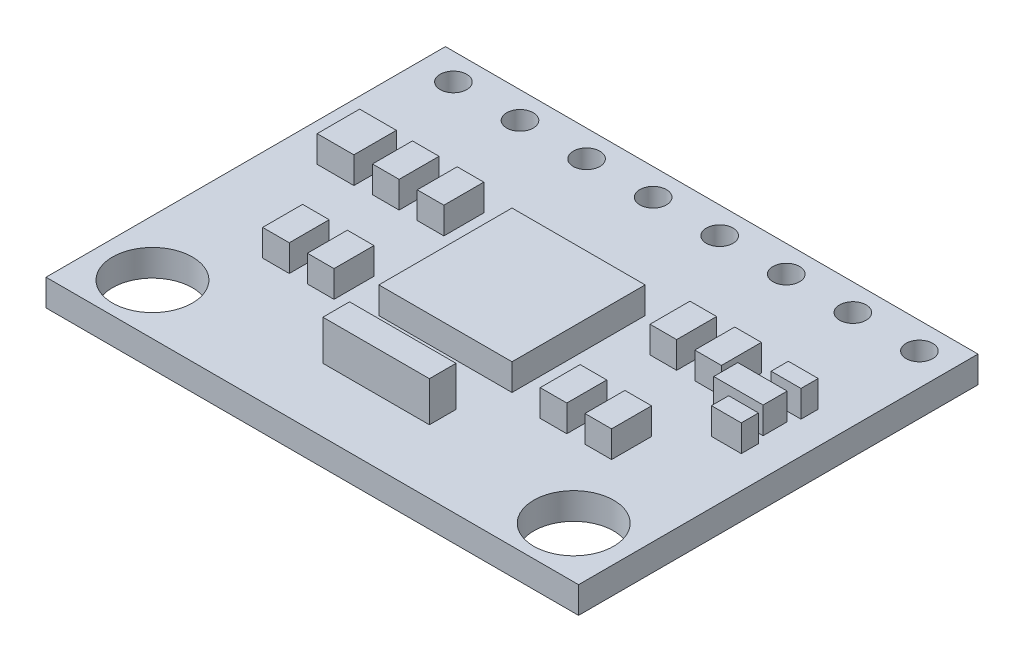
SolidWorks part; units mm, degrees
ref_plane "Front Plane" through (0, 0, 0) normal (0, 0, 1) x (1, 0, 0)
ref_plane "Top Plane" through (0, 0, 0) normal (0, 1, 0) x (1, 0, 0)
ref_plane "Right Plane" through (0, 0, 0) normal (1, 0, 0) x (0, 0, -1)
sketch "Sketch1" plane through (0, 0, 0) normal (0, 1, 0) x (1, 0, 0)
  line L1 (-10, 7.5) -> (10, 7.5)
  line L2 (-10, 7.5) -> (-10, -7.5)
  line L3 (-10, -7.5) -> (10, -7.5)
  line L4 (10, 7.5) -> (10, -7.5)
  line L5 (-10, 7.5) -> (10, -7.5) construction
  line L6 (-10, -7.5) -> (10, 7.5) construction
  point P0 (0, 0)
  dimension "D1" = 15
  dimension "D2" = 20
extrude "Boss-Extrude1" add sketch "Sketch1" along normal blind 1
sketch "Sketch2" plane through (0, 1, 0) normal (0, 1, 0) x (1, 0, 0)
  line L0 (10, 7.5) -> (-10, 7.5) construction
  line L1 (10, -7.5) -> (10, 7.5) construction
  circle A0 centre (8.8, 6.5) radius 0.5
  circle A1 centre (6.3, 6.5) radius 0.5
  circle A2 centre (3.8, 6.5) radius 0.5
  circle A3 centre (1.3, 6.5) radius 0.5
  circle A4 centre (-1.2, 6.5) radius 0.5
  circle A5 centre (-3.7, 6.5) radius 0.5
  circle A6 centre (-6.2, 6.5) radius 0.5
  circle A7 centre (-8.7, 6.5) radius 0.5
  dimension "D1" = 1
  dimension "D2" = 1
  dimension "D4" = 1.2
  dimension "D3" = 8
extrude "Cut-Extrude1" cut sketch "Sketch2" against normal blind 1
sketch "Sketch3" plane through (0, 1, 0) normal (0, 1, 0) x (1, 0, 0)
  circle A0 centre (7.9097, -5.5929) radius 1.5
  circle A1 centre (-7.9097, -5.5929) radius 1.5
  point P6 (0, 4.7739)
  dimension "D1" = 3
extrude "Cut-Extrude2" cut sketch "Sketch3" against normal blind 1
sketch "Sketch4" plane through (0, 1, 0) normal (0, 1, 0) x (1, 0, 0)
  line L1 (-2.5, 2.5) -> (2.5, 2.5)
  line L2 (-2.5, 2.5) -> (-2.5, -2.5)
  line L3 (-2.5, -2.5) -> (2.5, -2.5)
  line L4 (2.5, 2.5) -> (2.5, -2.5)
  line L5 (-2.5, 2.5) -> (2.5, -2.5) construction
  line L6 (-2.5, -2.5) -> (2.5, 2.5) construction
  point P0 (0, 0)
  dimension "D1" = 5
  dimension "D2" = 5
extrude "Boss-Extrude2" add sketch "Sketch4" along normal blind 1
sketch "Sketch5" plane through (0, 1, 0) normal (0, 1, 0) x (1, 0, 0)
  line L0 (0, 4.3428) -> (0, -4.6014) construction
  line L2 (-2, -4.1014) -> (2, -4.1014)
  line L3 (-2, -4.1014) -> (-2, -5.1014)
  line L4 (-2, -5.1014) -> (2, -5.1014)
  line L5 (2, -4.1014) -> (2, -5.1014)
  line L6 (-2, -4.1014) -> (2, -5.1014) construction
  line L7 (-2, -5.1014) -> (2, -4.1014) construction
  dimension "D1" = 4
  dimension "D2" = 1
extrude "Boss-Extrude3" add sketch "Sketch5" along normal blind 1.5
sketch "Sketch6" plane through (0, 1, 0) normal (0, 1, 0) x (1, 0, 0)
  line L0 (0, 8.0067) -> (0, -8.5671) construction
  line L1 (-13.5996, 0) -> (10.884, 0)
  line L2 (-3.8708, -2.8126) -> (-3.8708, -1.3126)
  line L3 (-4.8708, 2.8126) -> (-3.8708, 2.8126)
  line L4 (-4.8708, 2.8126) -> (-4.8708, 1.3126)
  line L5 (-4.8708, 1.3126) -> (-3.8708, 1.3126)
  line L6 (-3.8708, 2.8126) -> (-3.8708, 1.3126)
  line L9 (-6.5519, 2.8126) -> (-5.5519, 2.8126)
  line L10 (-6.5519, 2.8126) -> (-6.5519, 1.3126)
  line L11 (-6.5519, 1.3126) -> (-5.5519, 1.3126)
  line L12 (-5.5519, 2.8126) -> (-5.5519, 1.3126)
  line L15 (-4.8708, -2.8126) -> (-3.8708, -2.8126)
  line L16 (-4.8708, -2.8126) -> (-4.8708, -1.3126)
  line L17 (-4.8708, -1.3126) -> (-3.8708, -1.3126)
  line L18 (-5.5519, -2.8126) -> (-5.5519, -1.3126)
  line L19 (-6.5519, -2.8126) -> (-5.5519, -2.8126)
  line L20 (-6.5519, -2.8126) -> (-6.5519, -1.3126)
  line L21 (-6.5519, -1.3126) -> (-5.5519, -1.3126)
  line L22 (3.8708, -2.8126) -> (3.8708, -1.3126)
  line L23 (4.8708, -2.8126) -> (3.8708, -2.8126)
  line L24 (4.8708, -2.8126) -> (4.8708, -1.3126)
  line L25 (4.8708, -1.3126) -> (3.8708, -1.3126)
  line L26 (5.5519, -2.8126) -> (5.5519, -1.3126)
  line L27 (6.5519, -2.8126) -> (5.5519, -2.8126)
  line L28 (6.5519, -2.8126) -> (6.5519, -1.3126)
  line L29 (6.5519, -1.3126) -> (5.5519, -1.3126)
  line L30 (4.8708, 1.3126) -> (3.8708, 1.3126)
  line L31 (3.8708, 2.8126) -> (3.8708, 1.3126)
  line L32 (4.8708, 2.8126) -> (3.8708, 2.8126)
  line L33 (4.8708, 2.8126) -> (4.8708, 1.3126)
  line L34 (5.5519, 2.8126) -> (5.5519, 1.3126)
  line L35 (6.5519, 2.8126) -> (5.5519, 2.8126)
  line L36 (6.5519, 2.8126) -> (6.5519, 1.3126)
  line L37 (6.5519, 1.3126) -> (5.5519, 1.3126)
  point P5 (-4.3708, 2.0626)
  point P10 (-6.0519, 2.0626)
  dimension "D1" = 1.5
  dimension "D2" = 1.5
  dimension "D3" = 1
  dimension "D4" = 1
extrude "Boss-Extrude4" add sketch "Sketch6" along normal blind 1 contours L12 L9 L10 L11 | L6 L3 L4 L5 | L21 L20 L19 L18 | L17 L16 L15 L2 | L24 L25 L22 L23 | L28 L29 L26 L27 | L33 L32 L31 L30 | L37 L36 L35 L34
sketch "Sketch7" plane through (0, 1, 0) normal (0, 1, 0) x (1, 0, 0)
  line L1 (-8.5779, 2.8557) -> (-7.1985, 2.8557)
  line L2 (-8.5779, 2.8557) -> (-8.5779, 1.2608)
  line L3 (-8.5779, 1.2608) -> (-7.1985, 1.2608)
  line L4 (-7.1985, 2.8557) -> (-7.1985, 1.2608)
  line L5 (-8.5779, 2.8557) -> (-7.1985, 1.2608) construction
  line L6 (-8.5779, 1.2608) -> (-7.1985, 2.8557) construction
  line L7 (6.7675, 1.7134) -> (8.621, 1.7134)
  line L8 (6.7675, 1.7134) -> (6.7675, 0.8082)
  line L9 (6.7675, 0.8082) -> (8.621, 0.8082)
  line L10 (8.621, 1.7134) -> (8.621, 0.8082)
  line L13 (7.6727, 2.7048) -> (8.7934, 2.7048)
  line L14 (7.6727, 2.7048) -> (7.6727, 2.0583)
  line L15 (7.6727, 2.0583) -> (8.7934, 2.0583)
  line L16 (8.7934, 2.7048) -> (8.7934, 2.0583)
  line L19 (8.7934, -0.1832) -> (8.7934, 0.4634)
  line L20 (7.6727, 0.4634) -> (8.7934, 0.4634)
  line L21 (7.6727, -0.1832) -> (7.6727, 0.4634)
  line L22 (7.6727, -0.1832) -> (8.7934, -0.1832)
  point P0 (-7.8882, 2.0583)
  point P5 (8.233, 2.3815)
  point P7 (7.6942, 1.2608)
extrude "Boss-Extrude5" add sketch "Sketch7" along normal blind 1
